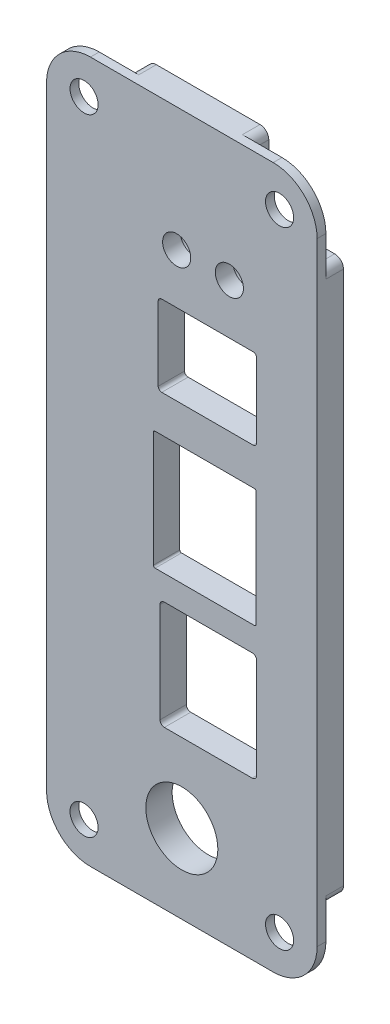
SolidWorks part; units mm, degrees
ref_plane "Front Plane" through (0, 0, 0) normal (0, 0, 1) x (1, 0, 0)
ref_plane "Top Plane" through (0, 0, 0) normal (0, 1, 0) x (1, 0, 0)
ref_plane "Right Plane" through (0, 0, 0) normal (1, 0, 0) x (0, 0, -1)
other "Configuration Table"
sketch "草图1" plane through (0, 0, 0) normal (0, 0, 1) x (1, 0, 0)
  line L0 (47.5, 0) -> (47.4, 0) construction
  line L1 (47.5, -35) -> (47.5, 35) construction
  line L2 (47.4, -34.9) -> (47.4, 34.9)
  line L3 (32, 40) -> (32, 39.9) construction
  line L4 (42.5, 40) -> (21.5, 40) construction
  line L5 (21.6, 39.9) -> (42.4, 39.9)
  line L8 (21.6, -39.9) -> (42.4, -39.9)
  line L9 (21.6, -39.9) -> (42.4, -39.9)
  line L10 (21.6, 39.9) -> (42.4, 39.9)
  line L15 (16.5, 0) -> (16.6, 0) construction
  line L16 (40.4138, -15.8026) -> (40.5139, -15.8026) construction
  line L17 (40.5139, -21.4776) -> (40.5139, -10.1276)
  line L18 (16.6, -34.9) -> (16.6, 34.9)
  line L19 (30.0139, -21.9776) -> (40.0139, -21.9776)
  line L20 (37.4138, 25.7931) -> (31.4138, 25.7931) construction
  line L22 (30.0139, -9.6276) -> (40.0139, -9.6276)
  line L25 (29.5139, -21.4776) -> (29.5139, -10.1276)
  line L31 (40.3644, -0.0546) -> (40.465, -0.0546) construction
  line L34 (40.465, 6.4954) -> (40.465, -6.6046)
  line L35 (34.6144, 6.5954) -> (34.6144, 6.6954) construction
  line L36 (28.9639, 6.6954) -> (40.265, 6.6954)
  line L38 (28.8639, -0.0546) -> (28.7639, -0.0546) construction
  line L39 (28.7639, 6.4954) -> (28.7639, -6.6046)
  line L40 (34.6139, -6.7046) -> (34.6139, -6.8046) construction
  line L41 (28.9639, -6.8046) -> (40.265, -6.8046)
  line L50 (40.5138, 11.3024) -> (40.5138, 19.7024)
  line L51 (29.7138, 20.1024) -> (40.1138, 20.1024)
  line L52 (29.3138, 11.3024) -> (29.3138, 19.7024)
  line L53 (29.7138, 10.9024) -> (40.1138, 10.9024)
  arc A0 (42.4, -39.9) -> (47.4, -34.9) centre (42.4, -34.9) ccw
  arc A1 (21.6, -39.9) -> (16.6, -34.9) centre (21.6, -34.9) cw
  arc A2 (47.4, 34.9) -> (42.4, 39.9) centre (42.4, 34.9) ccw
  arc A3 (16.6, 34.9) -> (21.6, 39.9) centre (21.6, 34.9) cw
  arc A4 (30.0139, -21.9776) -> (29.5139, -21.4776) centre (30.0139, -21.4776) cw
  arc A5 (40.0139, -21.9776) -> (40.5139, -21.4776) centre (40.0139, -21.4776) ccw
  arc A6 (40.5139, -10.1276) -> (40.0139, -9.6276) centre (40.0139, -10.1276) ccw
  arc A7 (29.5139, -10.1276) -> (30.0139, -9.6276) centre (30.0139, -10.1276) cw
  arc A8 (28.7639, 6.4954) -> (28.9639, 6.6954) centre (28.9639, 6.4954) cw
  arc A9 (40.465, 6.4954) -> (40.265, 6.6954) centre (40.265, 6.4954) ccw
  arc A10 (28.9639, -6.8046) -> (28.7639, -6.6046) centre (28.9639, -6.6046) cw
  arc A11 (40.265, -6.8046) -> (40.465, -6.6046) centre (40.265, -6.6046) ccw
  arc A12 (29.7138, 10.9024) -> (29.3138, 11.3024) centre (29.7138, 11.3024) cw
  arc A13 (40.1138, 10.9024) -> (40.5138, 11.3024) centre (40.1138, 11.3024) ccw
  arc A14 (40.5138, 19.7024) -> (40.1138, 20.1024) centre (40.1138, 19.7024) ccw
  arc A15 (29.3138, 19.7024) -> (29.7138, 20.1024) centre (29.7138, 19.7024) cw
  circle A16 centre (37.4138, 25.7931) radius 1.6
  circle A17 centre (31.4138, 25.7931) radius 1.6
  point P6 (0, 0)
  point P10 (0, 0)
  point P16 (32, -39.9)
  point P36 (40.5139, -15.8026)
  point P39 (35.0139, -21.9776)
  point P46 (35.0139, -9.6276)
  point P53 (29.5139, -15.8026)
  point P58 (40.4644, -0.0546)
  point P72 (40.465, -0.0546)
  point P78 (34.6144, 6.6954)
  point P84 (28.7639, -0.0546)
  point P89 (34.6139, -6.8046)
  point P112 (40.5138, 15.5024)
  point P117 (34.9138, 20.1024)
  point P118 (29.3138, 15.5024)
  point P123 (34.9138, 10.9024)
  dimension "D1" = 5
  dimension "D2" = 0.5
  dimension "D3" = 0.2
  dimension "D4" = 0.4
extrude "凸台-拉伸1" add sketch "草图1" against normal blind 3
sketch "草图2" plane through (0, 0, -3) normal (0, 0, -1) x (-1, 0, 0)
  line L0 (-16.6, -19) -> (-16.6, 19)
  line L2 (-16.6, -34.9) -> (-16.6, 34.9) construction
  line L3 (-16.6, -19) -> (-27.6, -19)
  line L4 (-27.6, -19) -> (-27.6, 19)
  line L5 (-27.6, 19) -> (-16.6, 19)
  point P5 (-16.6, 0)
extrude "切除-拉伸1" cut sketch "草图2" against normal blind 1
sketch "草图3" plane through (0, 0, -3) normal (0, 0, -1) x (-1, 0, 0)
  line L0 (-47.4, -31.4) -> (-38.9, -31.4)
  line L1 (-47.4, -34.9) -> (-47.4, 34.9) construction
  line L2 (-38.9, -31.4) -> (-38.9, -39.9)
  line L3 (-21.6, -39.9) -> (-42.4, -39.9) construction
  line L5 (-42.4, -39.9) -> (-38.9, -39.9)
  line L6 (-47.4, -34.9) -> (-47.4, -31.4)
  line L7 (-47.4, 0) -> (-16.6, 0) construction
  line L8 (-16.6, -19) -> (-16.6, 19) construction
  line L9 (-32, 0) -> (-32, -4.0641) construction
  line L10 (-47.4, 34.9) -> (-47.4, 31.4)
  line L11 (-42.4, 39.9) -> (-38.9, 39.9)
  line L12 (-38.9, 31.4) -> (-38.9, 39.9)
  line L13 (-47.4, 31.4) -> (-38.9, 31.4)
  line L15 (-16.6, 31.4) -> (-25.1, 31.4)
  line L16 (-25.1, 31.4) -> (-25.1, 39.9)
  line L17 (-21.6, 39.9) -> (-25.1, 39.9)
  line L18 (-16.6, 34.9) -> (-16.6, 31.4)
  line L19 (-16.6, -34.9) -> (-16.6, -31.4)
  line L20 (-21.6, -39.9) -> (-25.1, -39.9)
  line L21 (-25.1, -31.4) -> (-25.1, -39.9)
  line L22 (-16.6, -31.4) -> (-25.1, -31.4)
  arc A0 (-42.4, -39.9) -> (-47.4, -34.9) centre (-42.4, -34.9) cw
  arc A1 (-42.4, 39.9) -> (-47.4, 34.9) centre (-42.4, 34.9) ccw
  arc A2 (-21.6, 39.9) -> (-16.6, 34.9) centre (-21.6, 34.9) cw
  arc A3 (-21.6, -39.9) -> (-16.6, -34.9) centre (-21.6, -34.9) ccw
extrude "切除-拉伸2" cut sketch "草图3" against normal blind 2
sketch "草图4" plane through (0, 0, -1) normal (0, 0, -1) x (-1, 0, 0)
  line L0 (-47.4, 0) -> (-16.6, 0) construction
  line L1 (-47.4, -31.4) -> (-47.4, 31.4) construction
  line L2 (-16.6, -19) -> (-16.6, 19) construction
  line L3 (-32, 0) -> (-32, -3.4003) construction
  circle A0 centre (-20.8723, 35.6277) radius 1.6
  circle A2 centre (-20.8723, -35.6277) radius 1.6
  circle A3 centre (-43.1277, -35.6277) radius 1.6
  circle A4 centre (-43.1277, 35.6277) radius 1.6
extrude "切除-拉伸3" cut sketch "草图4" against normal through all
sketch "草图6" plane through (0, 0, -3) normal (0, 0, -1) x (-1, 0, 0)
  circle A0 centre (-37.4138, 25.7931) radius 2
  circle A1 centre (-31.4138, 25.7931) radius 2
extrude "切除-拉伸4" cut sketch "草图6" against normal blind 1
sketch "草图7" plane through (0, 0, 0) normal (0, 0, 1) x (1, 0, 0)
  line L0 (32, -39.9) -> (32, -21.9776) construction
  line L1 (30.0139, -21.9776) -> (40.0139, -21.9776) construction
  circle A1 centre (32, -30.9388) radius 4.1
extrude "切除-拉伸5" cut sketch "草图7" against normal through all
fillet "圆角1" radius 1 8 edges at (47.4, 31.4, -2) (47.4, -31.4, -2) (38.9, -39.9, -2) (25.1, -39.9, -2) (16.6, -31.4, -2) (38.9, 39.9, -2) (25.1, 39.9, -2) (16.6, 31.4, -2)
